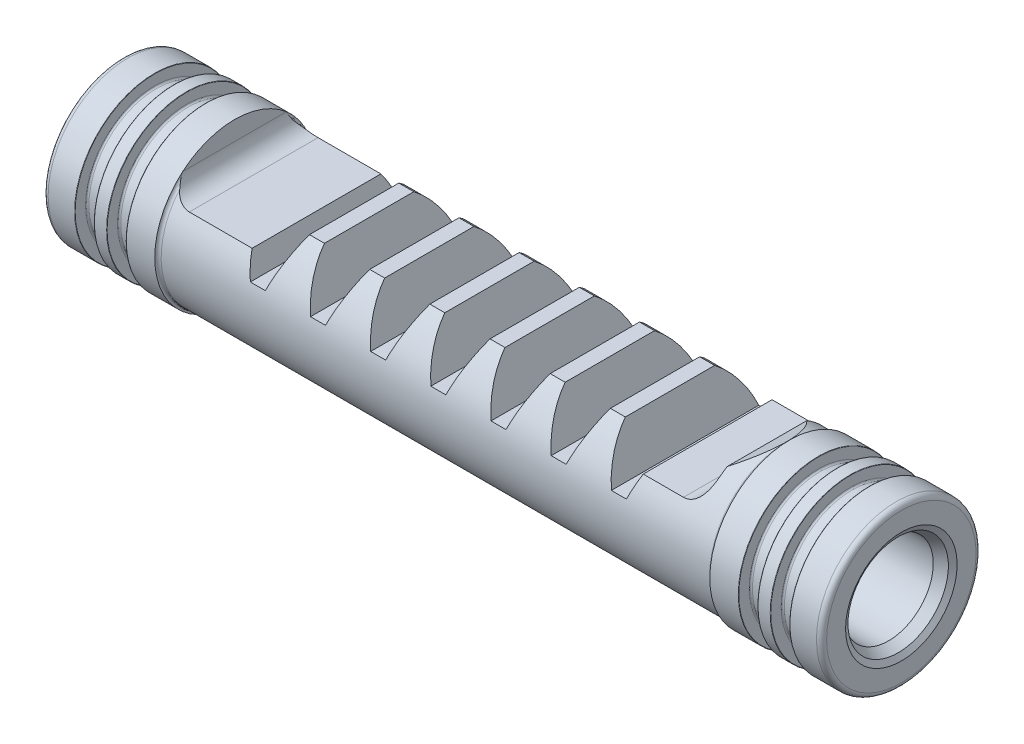
SolidWorks part; units mm, degrees
material "Простая углеродистая сталь"
ref_plane "Спереди" through (0, 0, 0) normal (0, 0, 1) x (1, 0, 0)
ref_plane "Сверху" through (0, 0, 0) normal (0, 1, 0) x (1, 0, 0)
ref_plane "Справа" through (0, 0, 0) normal (1, 0, 0) x (0, 0, -1)
sketch "Эскиз1" plane through (0, 0, 0) normal (0, 0, 1) x (1, 0, 0)
  line L0 (-137.6559, 0) -> (137.6559, 0) construction
  line L1 (-121.94, 17.4641) -> (-121.94, 23.4)
  line L2 (-120.34, 25) -> (-112.04, 25)
  line L3 (-111.94, 24.9) -> (-111.94, 21.65)
  line L4 (-111.44, 21.15) -> (-106.44, 21.15)
  line L5 (-105.94, 21.65) -> (-105.94, 24.9)
  line L6 (-105.84, 25) -> (-102.04, 25)
  line L7 (-101.94, 24.9) -> (-101.94, 21.65)
  line L8 (-101.44, 21.15) -> (-96.44, 21.15)
  line L9 (-95.94, 21.65) -> (-95.94, 24.9)
  line L10 (-95.84, 25) -> (-86.94, 25)
  line L11 (0, 34.36) -> (0, 0) construction
  line L12 (-121.94, 17.4641) -> (-120.94, 15.7321)
  line L13 (-120.94, 15.7321) -> (-117.94, 14)
  line L14 (-117.94, 14) -> (-93.94, 14)
  line L15 (-93.94, 14) -> (-85.8571, 0)
  line L16 (-85.8571, 0) -> (85.8571, 0)
  line L17 (-51.84, 25) -> (-51.84, 0) construction
  line L18 (51.84, 25) -> (51.84, 0) construction
  line L19 (93.94, 14) -> (85.8571, 0)
  line L20 (117.94, 14) -> (93.94, 14)
  line L21 (120.94, 15.7321) -> (117.94, 14)
  line L22 (121.94, 17.4641) -> (120.94, 15.7321)
  line L23 (95.94, 21.65) -> (95.94, 24.9)
  line L24 (101.44, 21.15) -> (96.44, 21.15)
  line L25 (101.94, 24.9) -> (101.94, 21.65)
  line L26 (105.84, 25) -> (102.04, 25)
  line L27 (105.94, 21.65) -> (105.94, 24.9)
  line L28 (111.44, 21.15) -> (106.44, 21.15)
  line L29 (111.94, 24.9) -> (111.94, 21.65)
  line L30 (120.34, 25) -> (112.04, 25)
  line L31 (121.94, 17.4641) -> (121.94, 23.4)
  line L32 (-85.94, 24) -> (85.94, 24)
  line L33 (86.94, 25) -> (95.84, 25)
  arc A0 (-95.94, 24.9) -> (-95.84, 25) centre (-95.84, 24.9) cw
  arc A1 (-102.04, 25) -> (-101.94, 24.9) centre (-102.04, 24.9) cw
  arc A2 (-105.94, 24.9) -> (-105.84, 25) centre (-105.84, 24.9) cw
  arc A3 (-112.04, 25) -> (-111.94, 24.9) centre (-112.04, 24.9) cw
  arc A4 (-96.44, 21.15) -> (-95.94, 21.65) centre (-96.44, 21.65) ccw
  arc A5 (-101.94, 21.65) -> (-101.44, 21.15) centre (-101.44, 21.65) ccw
  arc A6 (-106.44, 21.15) -> (-105.94, 21.65) centre (-106.44, 21.65) ccw
  arc A7 (-111.94, 21.65) -> (-111.44, 21.15) centre (-111.44, 21.65) ccw
  arc A8 (-121.94, 23.4) -> (-120.34, 25) centre (-120.34, 23.4) cw
  arc A9 (121.94, 23.4) -> (120.34, 25) centre (120.34, 23.4) ccw
  arc A10 (111.94, 21.65) -> (111.44, 21.15) centre (111.44, 21.65) cw
  arc A11 (106.44, 21.15) -> (105.94, 21.65) centre (106.44, 21.65) cw
  arc A12 (101.94, 21.65) -> (101.44, 21.15) centre (101.44, 21.65) cw
  arc A13 (96.44, 21.15) -> (95.94, 21.65) centre (96.44, 21.65) cw
  arc A14 (112.04, 25) -> (111.94, 24.9) centre (112.04, 24.9) ccw
  arc A15 (105.94, 24.9) -> (105.84, 25) centre (105.84, 24.9) ccw
  arc A16 (102.04, 25) -> (101.94, 24.9) centre (102.04, 24.9) ccw
  arc A17 (95.94, 24.9) -> (95.84, 25) centre (95.84, 24.9) ccw
  arc A18 (-85.94, 24) -> (-86.94, 25) centre (-85.94, 25) cw
  arc A19 (85.94, 24) -> (86.94, 25) centre (85.94, 25) ccw
  point P74 (0, 25)
  point P82 (0, 24)
  dimension "D3" = 0.1
  dimension "D4" = 0.5
  dimension "D5" = 1.6
  dimension "D19" = 1
  dimension "D1" = 6
  dimension "D2" = 6
  dimension "D6" = 60
  dimension "D7" = 28
  dimension "D8" = 60
  dimension "D9" = 28
  dimension "D10" = 30
  dimension "D11" = 4
  dimension "D12" = 1
  dimension "D13" = 70.1
  dimension "D14" = 103.68
  dimension "D15" = 50
  dimension "D16" = 42.3
  dimension "D17" = 10
  dimension "D18" = 20
  dimension "D20" = 48
  dimension "D21" = 35
revolve "Повернуть1" add sketch "Эскиз1" angle 360 about L0
sketch "Эскиз3" plane through (0, 0, 0) normal (0, 0, 1) x (1, 0, 0)
  line L0 (-86.94, 25) -> (-86.94, 19)
  line L1 (-80.94, 13) -> (-51.84, 13)
  line L2 (-51.84, 13) -> (-51.84, 19.5)
  line L3 (-51.84, 19.5) -> (51.84, 19.5)
  line L4 (51.84, 19.5) -> (51.84, 13)
  line L5 (51.84, 13) -> (73.8778, 13)
  line L6 (79.8778, 20.5) -> (85.94, 24)
  line L7 (85.94, 24) -> (-85.94, 24) construction
  line L8 (85.94, 24) -> (85.94, 25)
  line L9 (85.94, 25) -> (-86.94, 25)
  line L10 (79.8778, 20.5) -> (79.8778, 19)
  line L11 (-51.84, 25) -> (-51.84, 0) construction
  line L12 (51.84, 25) -> (51.84, 0) construction
  line L13 (-95.84, -25) -> (-86.94, -25) construction
  arc A0 (73.8778, 13) -> (79.8778, 19) centre (73.8778, 19) ccw
  arc A1 (-86.94, 19) -> (-80.94, 13) centre (-80.94, 19) ccw
  dimension "D2" = 12
  dimension "D4" = 6
  dimension "D1" = 3.5
  dimension "D3" = 44.5
  dimension "D5" = 30
extrude "Вырез-Вытянуть1" cut sketch "Эскиз3" against normal through all and the other way through all
sketch "Эскиз5" plane through (0, 0, 0) normal (0, 0, 1) x (1, 0, 0)
  line L0 (-48.3517, -24) -> (-39.64, -17.9)
  line L1 (-85.94, -24) -> (85.94, -24) construction
  line L2 (-39.64, -17.9) -> (-24.64, -17.9)
  line L3 (-24.64, -17.9) -> (-14.7491, -21.5)
  line L4 (-14.7491, -21.5) -> (91.94, -21.5)
  line L5 (91.94, -21.5) -> (91.94, -24)
  line L6 (86.94, -25) -> (95.84, -25) construction
  line L7 (92.94, -25) -> (-48.3517, -25)
  line L8 (-48.3517, -25) -> (-48.3517, -24)
  line L9 (-121.94, 23.4) -> (-121.94, -23.4) construction
  line L10 (121.94, -23.4) -> (121.94, 23.4) construction
  arc A0 (91.94, -24) -> (92.94, -25) centre (92.94, -24) ccw
  dimension "D8" = 1
  dimension "D1" = 35
  dimension "D2" = 3.6
  dimension "D3" = 7.1
  dimension "D4" = 15
  dimension "D5" = 20
  dimension "D6" = 97.3
  dimension "D7" = 30
extrude "Вырез-Вытянуть3" cut sketch "Эскиз5" against normal through all and the other way through all
sketch "Эскиз4" plane through (0, 0, 0) normal (0, 0, 1) x (1, 0, 0)
  line L0 (-54.2058, 6.5) -> (-49.4742, 19.5)
  line L1 (-49.4742, 19.5) -> (-63.6308, 19.5)
  line L2 (-63.6308, 19.5) -> (-58.8992, 6.5)
  line L3 (-58.8992, 6.5) -> (-54.2058, 6.5)
  line L4 (51.84, 19.5) -> (-51.84, 19.5) construction
  line L5 (-61.265, 13) -> (-51.84, 13) construction
  line L6 (-51.84, 13) -> (-80.94, 13) construction
  dimension "D1" = 9.425
  dimension "D2" = 40
extrude "Вырез-Вытянуть2" cut sketch "Эскиз4" against normal through all and the other way through all
pattern_linear "Линейный массив2" count 7 spacing 18.85 along (1, 0, 0) of "Вырез-Вытянуть2"
